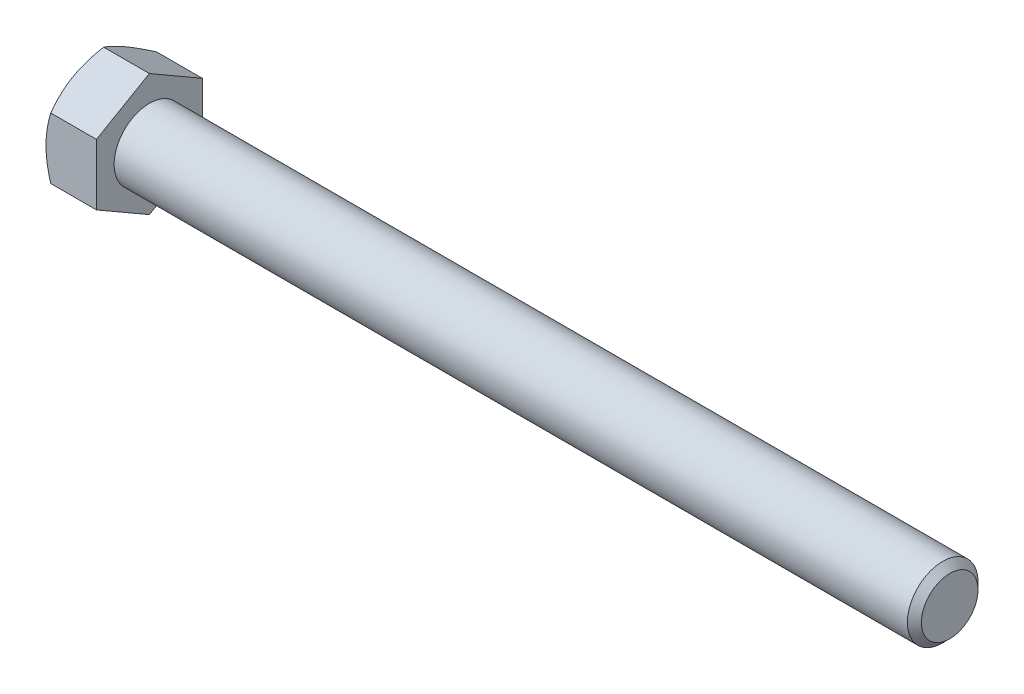
SolidWorks part; units mm, degrees
extrude "BaseHead" add sketch "Sketch1" along normal blind 6.8072
sketch "Sketch1" plane through (0, 0, 0) normal (1, 0, 0) x (0, 0, -1)
  line L0 (7.1374, 4.1208) -> (7.1374, -4.1208)
  line L1 (-7.1374, 4.1208) -> (-7.1374, -4.1208)
  line L2 (7.1374, -4.1208) -> (0, -8.2416)
  line L3 (0, -8.2416) -> (-7.1374, -4.1208)
  line L4 (7.1374, 4.1208) -> (0, 8.2416)
  line L5 (0, 8.2416) -> (-7.1374, 4.1208)
  dimension "Width_flats" = 14.2748
  dimension "D2" = 120
  dimension "D3" = 7.1374
  dimension "D4" = 7.1374
  dimension "D5" = 7.1374
ref_plane "Plane1" through (0, 0, 0) normal (0, 0, 1) x (1, 0, 0)
ref_plane "Plane2" through (0, 0, 0) normal (0, 1, 0) x (1, 0, 0)
ref_plane "Plane3" through (0, 0, 0) normal (1, 0, 0) x (0, 0, -1)
sketch "BodySke" plane through (0, 0, 0) normal (0, 0, 1) x (1, 0, 0)
  line L0 (0, 4.1208) -> (0, -4.1208) construction
  line L1 (0, 0) -> (114.7572, 0)
  line L2 (0, 0) -> (0, 4.7625)
  line L3 (0, 4.7625) -> (113.811, 4.7625)
  line L4 (114.7572, 0) -> (114.7572, 3.8163)
  line L5 (6.8072, 8.2416) -> (6.8072, 4.1208) construction
  line L6 (114.7572, 3.8163) -> (113.811, 4.7625)
  line L7 (0, 0) -> (96.52, 0) construction
  line L8 (114.7572, -3.8163) -> (113.811, -4.7625) construction
  line L9 (0, -4.7625) -> (113.811, -4.7625) construction
  line L10 (8.3947, 15.24) -> (8.3947, -2.54) construction
  line L11 (71.5772, 15.24) -> (71.5772, -2.54) construction
  line L12 (6.8072, 4.1208) -> (6.8072, -4.1208) construction
  dimension "Diameter" = 9.525
revolve "BaseBody" add sketch "BodySke" angle 360 about L7
cosmetic thread "ThreadCosmetic" parameters "Thread_length"=43.18, "Thread_minor"=7.6327
sketch "Sketch3" plane through (0, 0, 0) normal (0, 0, 1) x (1, 0, 0)
  line L0 (0, 7.1374) -> (4.3037, 14.5916)
  line L1 (0, 8.2416) -> (0, 4.1208) construction
  line L2 (4.3037, 14.5916) -> (4.3037, 20.9416)
  line L3 (4.3037, 20.9416) -> (-12.7, 20.9416)
  line L4 (-12.7, 20.9416) -> (-12.7, 7.1374)
  line L5 (-12.7, 7.1374) -> (0, 7.1374)
  line L6 (0, 0) -> (99.06, 0) construction
  line L7 (6.8072, 8.2416) -> (0, 8.2416) construction
  dimension "D1" = 7.1374
  dimension "D2" = 6.35
  dimension "D3" = 12.7
  dimension "D4" = 6.35
  dimension "Head_ch_ang" = 30
revolve "HeadChamfer" cut sketch "Sketch3" angle 360 about L6
fillet "HeadFillet" [suppressed] radius 0.762
sketch "ThdSchSke" plane through (0, 0, 0) normal (0, 0, 1) x (1, 0, 0)
  line L0 (71.5772, -3.8163) -> (70.9147, -4.7625)
  line L1 (71.5772, -3.8163) -> (72.2397, -4.7625)
  line L2 (72.2397, -4.7625) -> (72.2397, -5.9531)
  line L3 (-3.175, 0) -> (5.1513, 0) construction
  line L5 (72.2397, -5.9531) -> (70.9147, -5.9531)
  line L6 (70.9147, -5.9531) -> (70.9147, -4.7625)
  dimension "Thread_minor" = 7.6327
  dimension "Diameter" = 9.525
  dimension "Start" = 71.5772
revolve "ThreadSchematic" [suppressed] cut sketch "ThdSchSke" angle 360 about L3
pattern_linear "ThdSchPat" [suppressed]
equation "\"D3@Sketch1\" = \"Width_flats@Sketch1\" / 2"
equation "\"D4@Sketch1\" = \"D3@Sketch1\""
equation "\"D5@Sketch1\" = \"D4@Sketch1\""
equation "\"Thread_minor@ThreadCosmetic\" = \"Minor_dia@BodySke\""
equation "\"D1@Sketch3\" = \"Width_flats@Sketch1\" / 2"
equation "\"Thread_length@ThreadCosmetic\" = ((sgn( (\"Length@BodySke\" - \"Advance@BodySke\" ) - \"Thread_nom@BodySke\" )-1)*( (\"Length@BodySke\" - \"Advance@BodySke\" ) - \"Thread_nom@BodySke\" ))/-2+ \"Thread_nom@BodySke\""
equation "\"Thread_minor@ThdSchSke\" = \"Minor_dia@BodySke\""
equation "\"Diameter@ThdSchSke\" = \"Diameter@BodySke\""
equation "\"Overcut@ThdSchSke\" = \"Diameter@BodySke\" * 1.25"
equation "\"Start@ThdSchSke\" = \"Head_ht@BaseHead\" + \"Length@BodySke\" - \"Thread_length@ThreadCosmetic\"  '---Non-countersunk---"
equation "\"Num_threads@ThdSchPat\" = int( \"Thread_length@ThreadCosmetic\" / \"Advance@BodySke\" + 0.999 )  + 1"
equation "\"Advance@ThdSchPat\" = \"Thread_length@ThreadCosmetic\" /  (\"Num_threads@ThdSchPat\" - 1) 'relax it"
equation "\"Num_threads@ThdSchPat\" = \"Num_threads@ThdSchPat\" - sgn( \"Num_threads@ThdSchPat\" - 1) '---chamfered tips only---"
